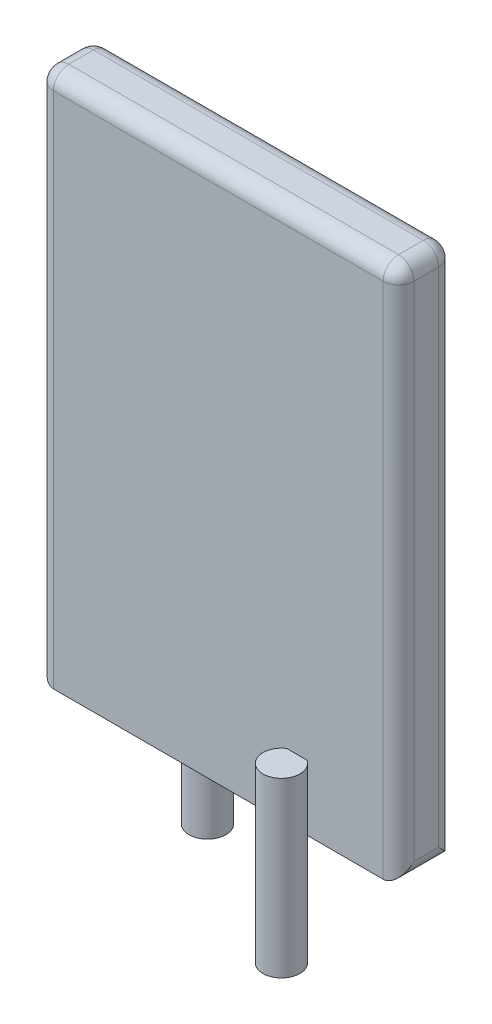
SolidWorks part; units mm, degrees
ref_plane "Front" through (0, 0, 0) normal (0, 0, 1) x (1, 0, 0)
ref_plane "Top" through (0, 0, 0) normal (0, 1, 0) x (1, 0, 0)
ref_plane "Right" through (0, 0, 0) normal (1, 0, 0) x (0, 0, -1)
sketch "Эскиз1" plane through (0, 0, 0) normal (0, 0, 1) x (1, 0, 0)
  line L1 (-5.85, 8.65) -> (5.85, 8.65)
  line L2 (-5.85, 8.65) -> (-5.85, -8.65)
  line L3 (-5.85, -8.65) -> (5.85, -8.65)
  line L4 (5.85, 8.65) -> (5.85, -8.65)
  line L5 (0, -8.65) -> (0, 8.65) construction
  line L6 (-5.85, 0) -> (5.85, 0) construction
  point P4 (0, 0)
  point P224 (0, 0)
  dimension "D1" = 11.7
  dimension "D2" = 17.3
extrude "Бобышка-Вытянуть1" add sketch "Эскиз1" along normal mid plane 1.8
fillet "Скругление1" radius 0.5 10 edges at (0, 8.65, -0.9) (0, 8.65, 0.9) (5.85, 0, -0.9) (5.85, 0, 0.9) (-5.85, 0, -0.9) (-5.85, 0, 0.9) (-5.85, -8.65, 0) (5.85, -8.65, 0) (5.85, 8.65, 0) (-5.85, 8.65, 0)
ref_plane "Плоскость1" through (2.55, 0, 0) normal (1, 0, 0) x (0, 0, -1)
sketch "Эскиз3" plane through (2.55, 0, 0) normal (1, 0, 0) x (0, 0, -1)
  line L0 (-0.8, -6.5405) -> (-1.4, -6.5405)
  line L2 (-1.4, -6.5405) -> (-1.4, -12.15)
  line L3 (-1.4, -12.15) -> (-0.8, -12.15)
  line L4 (-0.8, -12.15) -> (-0.8, -6.5405)
  line L5 (0.9, -8.65) -> (-0.9, -8.65) construction
  line L6 (-1.4, -2.2227) -> (-1.4, -15.6279) construction
  line L9 (-0.9, -8.65) -> (-0.9, 8.15) construction
  point P0 (0, 0)
  point P6 (0, 0)
  point P10 (0, 0)
  dimension "D1" = 0.6
  dimension "D2" = 3.5
  dimension "D3" = 0.1
revolve "Повернуть2" add sketch "Эскиз3" angle 360 about L6
move or copy body "Тело-Переместить/Копировать1" bodies to move or copy 102 copy yes number of copies 1 translate (-5.1, 0, -2.7)
